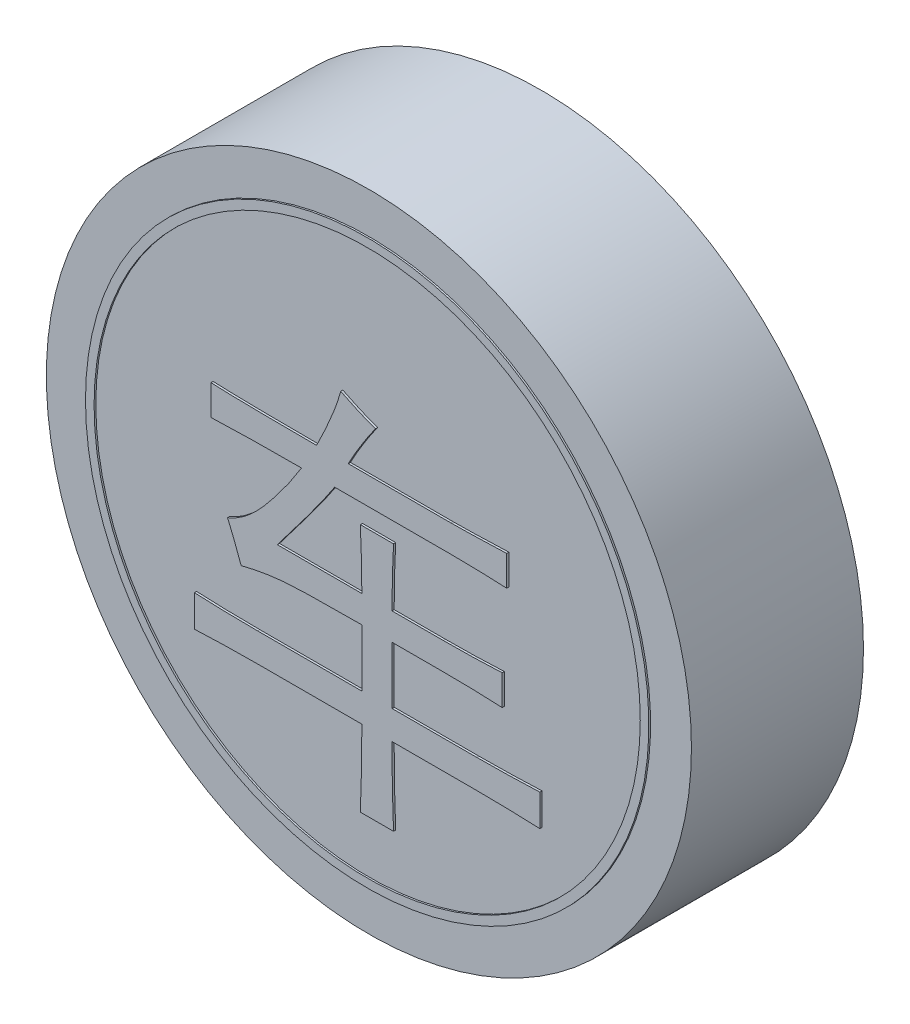
SolidWorks part; units mm, degrees
ref_plane "前视基准面" through (0, 0, 0) normal (0, 0, 1) x (1, 0, 0)
ref_plane "上视基准面" through (0, 0, 0) normal (0, 1, 0) x (1, 0, 0)
ref_plane "右视基准面" through (0, 0, 0) normal (1, 0, 0) x (0, 0, -1)
other "Configuration Table"
sketch "草图1" plane through (0, 0, 0) normal (0, 0, 1) x (1, 0, 0)
  circle A0 centre (0, 0) radius 15
  dimension "D1" = 30
extrude "Diameter30_Height8" add sketch "草图1" against normal blind 8
sketch "草图2" plane through (0, 0, 0) normal (0, 0, 1) x (1, 0, 0)
  text T0 "车" font "SimHei" height 12
extrude "Character_车" add sketch "草图2" along normal blind 0.1
sketch "草图3" plane through (0, 0, 0) normal (0, 0, 1) x (1, 0, 0)
  circle A0 centre (0, 0) radius 13.1
  circle A1 centre (0, 0) radius 12.7
extrude "Ink_ring" add sketch "草图3" along normal blind 0.08
